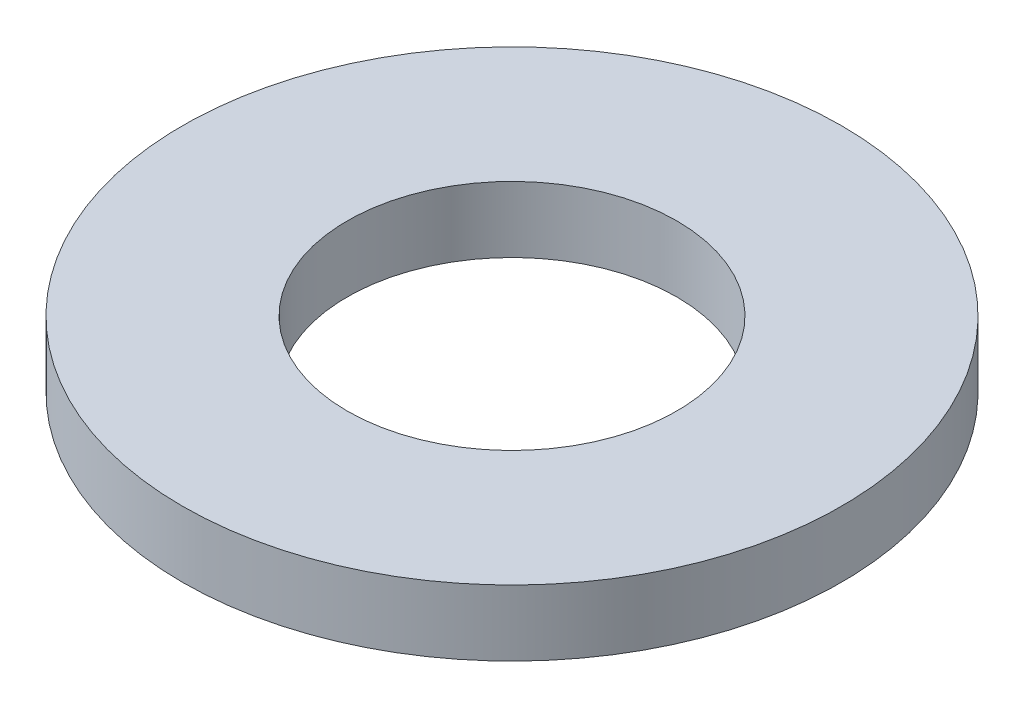
SolidWorks part; units mm, degrees
ref_plane "Front Plane" through (0, 0, 0) normal (0, 0, 1) x (1, 0, 0)
ref_plane "Top Plane" through (0, 0, 0) normal (0, 1, 0) x (1, 0, 0)
ref_plane "Right Plane" through (0, 0, 0) normal (1, 0, 0) x (0, 0, -1)
sketch "Sketch1" plane through (0, 0, 0) normal (0, 1, 0) x (1, 0, 0)
  circle A0 centre (0, 0) radius 8
  circle A1 centre (0, 0) radius 4
  dimension "D1" = 8
  dimension "D2" = 16
extrude "Boss-Extrude1" add sketch "Sketch1" along normal blind 1.6
